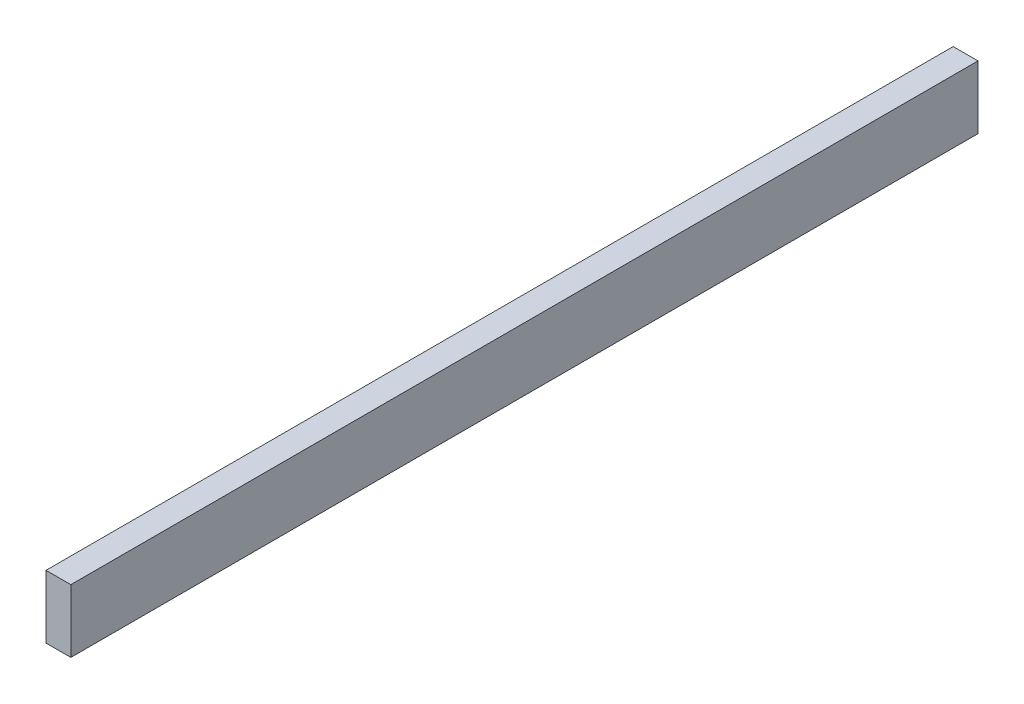
SolidWorks part; units mm, degrees
ref_plane "Front Plane" through (0, 0, 0) normal (0, 0, 1) x (1, 0, 0)
ref_plane "Top Plane" through (0, 0, 0) normal (0, 1, 0) x (1, 0, 0)
ref_plane "Right Plane" through (0, 0, 0) normal (1, 0, 0) x (0, 0, -1)
sketch "Sketch1" plane through (0, 0, 0) normal (0, 0, 1) x (1, 0, 0)
  line L1 (-212, 22.86) -> (-194, 22.86)
  line L2 (-212, 22.86) -> (-212, -22.86)
  line L3 (-212, -22.86) -> (-194, -22.86)
  line L4 (-194, 22.86) -> (-194, -22.86)
  dimension "D1" = 18
extrude "Boss-Extrude1" add sketch "Sketch1" against normal up to surface (552 mm away)
sketch "Sketch2" plane through (0, 0, -552) normal (0, 0, -1) x (-1, 0, 0)
  line L0 (212, 22.86) -> (194, 22.86) construction
  line L1 (212, -22.86) -> (194, -22.86)
  line L2 (212, -22.86) -> (212, 22.86)
  line L3 (212, 22.86) -> (194, 22.86)
  line L4 (194, -22.86) -> (194, 22.86)
  line L5 (194, 22.86) -> (194, -22.86) construction
extrude "Boss-Extrude2" add sketch "Sketch2" along normal up to surface (106 mm away)
